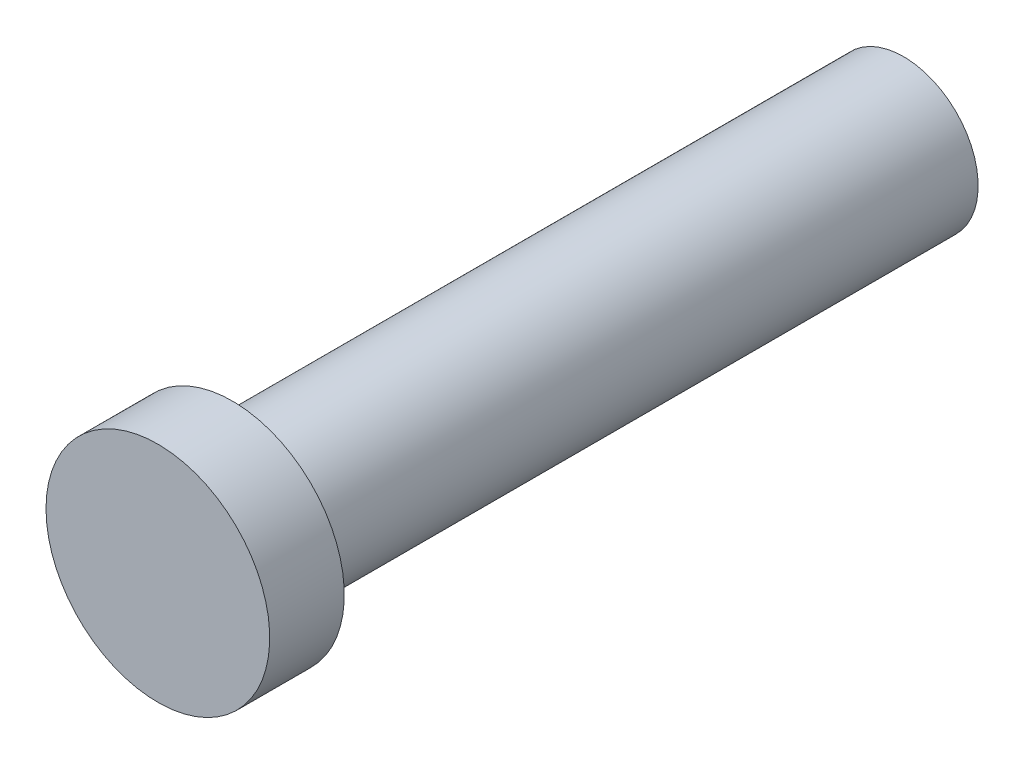
SolidWorks part; units mm, degrees
ref_plane "Přední rovina" through (0, 0, 0) normal (0, 0, 1) x (1, 0, 0)
ref_plane "Horní rovina" through (0, 0, 0) normal (0, 1, 0) x (1, 0, 0)
ref_plane "Pravá rovina" through (0, 0, 0) normal (1, 0, 0) x (0, 0, -1)
sketch "Skica1" plane through (0, 0, 0) normal (0, 0, 1) x (1, 0, 0)
  circle A0 centre (0, 0) radius 5
  dimension "D1" = 10
extrude "Přidat vysunutím1" add sketch "Skica1" along normal blind 45
sketch "Skica2" plane through (0, 0, 45) normal (0, 0, 1) x (1, 0, 0)
  circle A0 centre (0, 0) radius 7.5
  dimension "D1" = 15
extrude "Přidat vysunutím2" add sketch "Skica2" along normal blind 5
